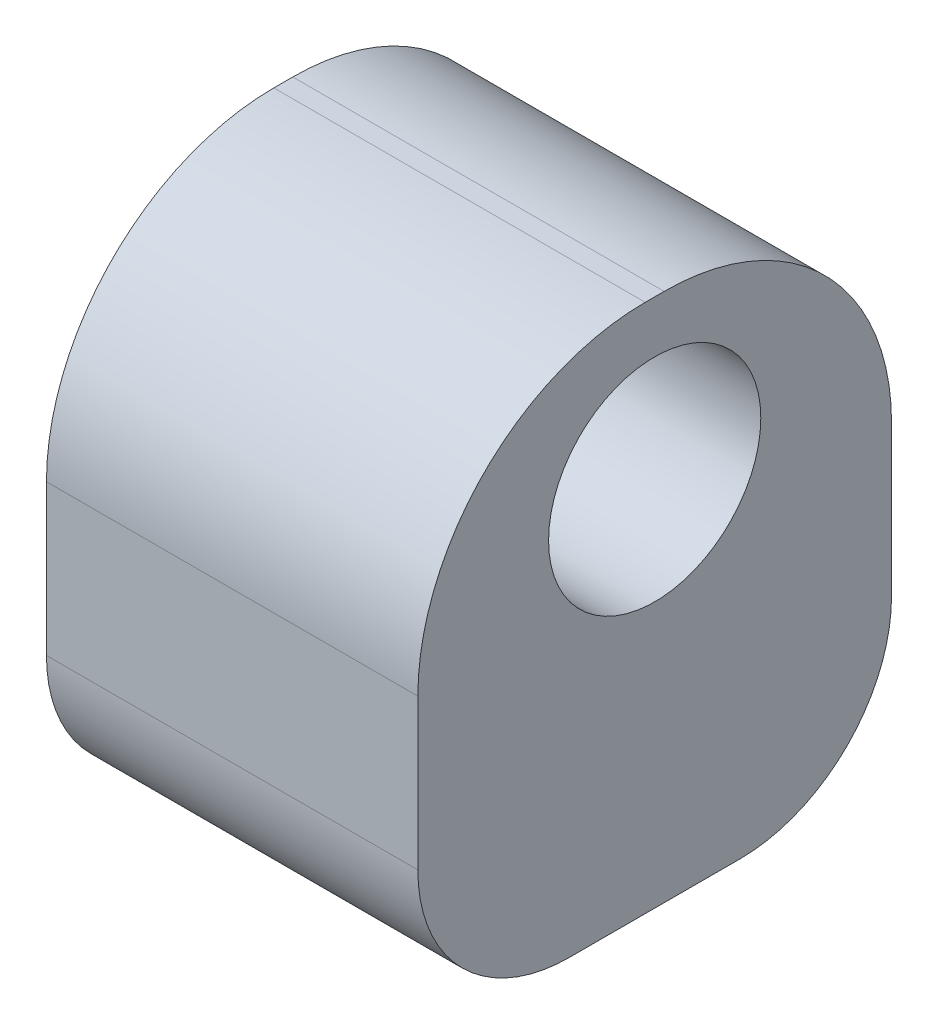
SolidWorks part; units mm, degrees
ref_plane "Front Plane" through (0, 0, 0) normal (1, 0, 0) x (0, 1, 0)
ref_plane "Top Plane" through (0, 0, 0) normal (0, 0, 1) x (0, 1, 0)
ref_plane "Right Plane" through (0, 0, 0) normal (0, 1, 0) x (-1, 0, 0)
sketch "Sketch1" plane through (0, 0, 0) normal (1, 0, 0) x (0, 1, 0)
  line L1 (0, 0) -> (-50.8, 0)
  line L2 (0, 0) -> (0, 9.525)
  line L3 (0, 9.525) -> (-50.8, 9.525)
  line L4 (-50.8, 0) -> (-50.8, 9.525)
  dimension "D1" = 50.8
  dimension "D2" = 9.525
extrude "Boss-Extrude1" add sketch "Sketch1" along normal blind 12.446
sketch "Sketch6" plane through (12.446, 0, 0) normal (1, 0, 0) x (0, 1, 0)
  line L0 (-50.8, 4.7625) -> (0, 4.7625) construction
  line L1 (-50.8, 9.525) -> (-50.8, 0) construction
  line L2 (0, 0) -> (0, 9.525) construction
  circle A0 centre (-44.45, 4.7625) radius 1.905
  dimension "D1" = 3.81
  dimension "D2" = 6.35
extrude "Cut-Extrude4" cut sketch "Sketch6" against normal up to vertex (12.446 mm away)
sketch "Sketch7" plane through (12.446, 0, 0) normal (1, 0, 0) x (0, 1, 0)
  circle A0 centre (-44.45, 4.7625) radius 3.556
  dimension "D1" = 7.112
extrude "Cut-Extrude5" cut sketch "Sketch7" against normal blind 5.08
sketch "Sketch8" plane through (12.446, 0, 0) normal (1, 0, 0) x (0, 1, 0)
  line L0 (-38.1, 0) -> (-38.1, 9.525)
  line L4 (0, 9.525) -> (-50.8, 9.525)
  line L5 (-50.8, 9.525) -> (-50.8, 0)
  line L6 (-50.8, 0) -> (0, 0)
  line L7 (0, 0) -> (0, 9.525)
  line L8 (0, 9.525) -> (-38.1, 9.525)
  line L10 (-38.1, 0) -> (0, 0)
  line L11 (0, 0) -> (0, 9.525)
  dimension "D1" = 0
extrude "Cut-Extrude6" cut sketch "Sketch8" against normal up to vertex (12.446 mm away) up to point (0, 0, 0)
fillet "Fillet2" radius 2.54 2 edges at (6.223, -38.1, 9.525) (6.223, -38.1, 0)
sketch "Sketch9" plane through (12.446, 0, 0) normal (1, 0, 0) x (0, 1, 0)
  line L0 (-40.64, 0) -> (-38.1, 2.54)
  line L2 (-38.1, 6.985) -> (-40.64, 9.525)
  arc A0 (-40.64, 0) -> (-38.1, 2.54) centre (-40.64, 2.54) ccw construction
  arc A1 (-38.1, 6.985) -> (-40.64, 9.525) centre (-40.64, 6.985) ccw construction
  arc A2 (-40.64, 0) -> (-38.1, 2.54) centre (-40.64, 2.54) ccw
  arc A3 (-38.1, 6.985) -> (-40.64, 9.525) centre (-40.64, 6.985) ccw
extrude "Cut-Extrude7" cut sketch "Sketch9" against normal up to vertex (12.446 mm away) up to point (0, -40.64, 0)
sketch "Sketch10" plane through (12.446, 0, 0) normal (1, 0, 0) x (0, 1, 0)
  line L0 (-38.1, 4.7625) -> (-41.3216, 4.7625) construction
  line L1 (-38.1, 6.985) -> (-38.1, 2.54) construction
fillet "Fillet4" radius 5.08 2 edges at (6.223, -38.1, 6.985) (6.223, -38.1, 2.54)
sketch "Sketch11" plane through (0, -50.8, 0) normal (0, -1, 0) x (1, 0, 0)
  line L4 (0, 9.525) -> (0, 0)
  line L5 (0, 0) -> (12.446, 0)
  line L6 (12.446, 0) -> (12.446, 9.525)
  line L7 (12.446, 9.525) -> (0, 9.525)
  line L8 (0, 9.525) -> (0, 0)
  line L9 (0, 0) -> (12.446, 0)
  line L10 (12.446, 0) -> (12.446, 9.525)
  line L11 (12.446, 9.525) -> (0, 9.525)
  dimension "D1" = 0
extrude "Boss-Extrude2" add sketch "Sketch11" along normal blind 6.35
sketch "Sketch12" plane through (12.446, 0, 0) normal (1, 0, 0) x (0, 1, 0)
  line L0 (-40.64, 9.525) -> (-57.15, 9.525) construction
  line L1 (-57.15, 0) -> (-56.896, 0)
  line L2 (-57.15, 0) -> (-57.15, 9.525)
  line L3 (-57.15, 9.525) -> (-56.896, 9.525)
  line L4 (-56.896, 0) -> (-56.896, 9.525)
  dimension "D1" = 0.254
extrude "Cut-Extrude8" cut sketch "Sketch12" against normal up to vertex
sketch "Sketch13" plane through (12.446, 0, 0) normal (1, 0, 0) x (0, 1, 0)
  line L0 (-39.153, 7.9775) -> (-39.153, 1.5475)
  line L1 (-38.1, 4.8808) -> (-38.1, 4.6442) construction
  line L2 (-38.1, 4.8808) -> (-38.1, 4.6442)
  arc A0 (-38.1, 4.8808) -> (-39.5879, 8.4729) centre (-43.18, 4.8808) ccw construction
  arc A1 (-39.5879, 1.0521) -> (-38.1, 4.6442) centre (-43.18, 4.6442) ccw construction
  arc A2 (-38.1, 4.8808) -> (-39.153, 7.9775) centre (-43.18, 4.8808) ccw
  arc A3 (-39.153, 1.5475) -> (-38.1, 4.6442) centre (-43.18, 4.6442) ccw
extrude "Cut-Extrude9" cut sketch "Sketch13" against normal up to vertex
sketch "Sketch14" plane through (12.446, 0, 0) normal (1, 0, 0) x (0, 1, 0)
  line L0 (-40.64, 12.7) -> (-39.153, 12.7)
  line L1 (-56.896, 0) -> (-40.64, 0)
  line L2 (-56.896, 0) -> (-56.896, -3.175)
  line L3 (-56.896, -3.175) -> (-40.64, -3.175)
  line L5 (-56.896, 9.525) -> (-40.64, 9.525)
  line L6 (-39.153, 1.5475) -> (-39.153, 7.9775)
  line L7 (-39.5879, 8.4729) -> (-40.64, 9.525)
  line L8 (-40.64, 9.525) -> (-56.896, 9.525)
  line L9 (-56.896, 9.525) -> (-56.896, 0)
  line L10 (-56.896, 0) -> (-40.64, 0)
  line L11 (-40.64, 0) -> (-39.5879, 1.0521)
  line L13 (-39.5879, 8.4729) -> (-40.64, 9.525)
  line L14 (-40.64, 9.525) -> (-56.896, 9.525)
  line L16 (-56.896, 0) -> (-40.64, 0)
  line L17 (-40.64, 0) -> (-39.5879, 1.0521)
  line L18 (-56.896, 9.525) -> (-56.896, 12.7)
  line L19 (-56.896, 12.7) -> (-40.64, 12.7)
  line L21 (-39.153, 12.7) -> (-39.153, 7.9775)
  line L22 (-39.153, 1.5475) -> (-39.153, -3.175)
  line L23 (-39.153, -3.175) -> (-40.64, -3.175)
  arc A2 (-39.153, 7.9775) -> (-39.5879, 8.4729) centre (-43.18, 4.8808) ccw
  arc A3 (-39.5879, 1.0521) -> (-39.153, 1.5475) centre (-43.18, 4.6442) ccw
  arc A4 (-39.153, 7.9775) -> (-39.5879, 8.4729) centre (-43.18, 4.8808) ccw
  arc A5 (-39.5879, 1.0521) -> (-39.153, 1.5475) centre (-43.18, 4.6442) ccw
  arc M18 (-39.153, 7.9775) -> (-39.5879, 8.4729) centre (-43.18, 4.8808) ccw
  line M19 (-39.5879, 8.4729) -> (-40.64, 9.525)
  line M20 (-40.64, 9.525) -> (-56.896, 9.525)
  line M22 (-56.896, 0) -> (-40.64, 0)
  line M23 (-40.64, 0) -> (-39.5879, 1.0521)
  arc M24 (-39.5879, 1.0521) -> (-39.153, 1.5475) centre (-43.18, 4.6442) ccw
  dimension "D2" = 3.175
  dimension "D3" = 3.175
  dimension "D1" = 0
extrude "Boss-Extrude3" add sketch "Sketch14" against normal up to surface (12.446 mm away) contours L21 L0 L19 L18 M20 M19 M18 | L23 L22 L2 L3 M24 M23 M22 up to face at (0, -44.45, 2.8575)
fillet "Fillet6" radius 7.62 2 edges at (6.223, -39.153, 12.7) (6.223, -39.153, -3.175)
fillet "Fillet7" radius 5.08 2 edges at (6.223, -56.896, -3.175) (6.223, -56.896, 12.7)
